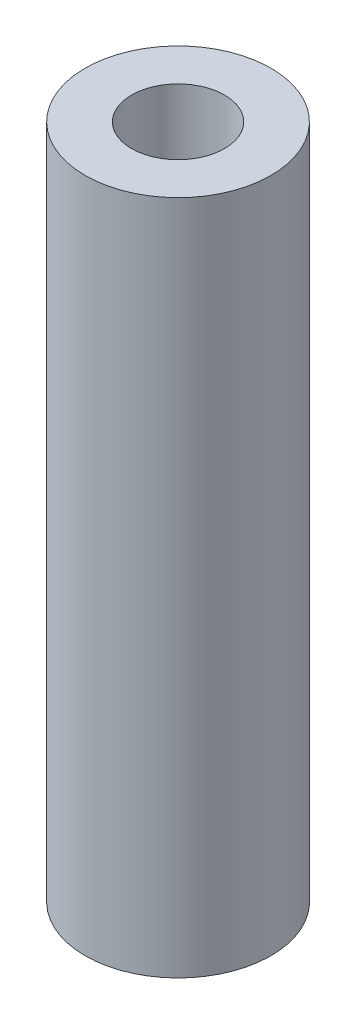
SolidWorks part; units mm, degrees
ref_plane "Front Plane" through (0, 0, 0) normal (0, 0, 1) x (1, 0, 0)
ref_plane "Top Plane" through (0, 0, 0) normal (0, 1, 0) x (1, 0, 0)
ref_plane "Right Plane" through (0, 0, 0) normal (1, 0, 0) x (0, 0, -1)
sketch "Sketch1" plane through (0, 0, 0) normal (0, 1, 0) x (1, 0, 0)
  circle A0 centre (0, 0) radius 5.5
  circle A1 centre (0, 0) radius 11
  dimension "D1" = 11
  dimension "D2" = 22
extrude "Boss-Extrude1" add sketch "Sketch1" along normal mid plane 80
